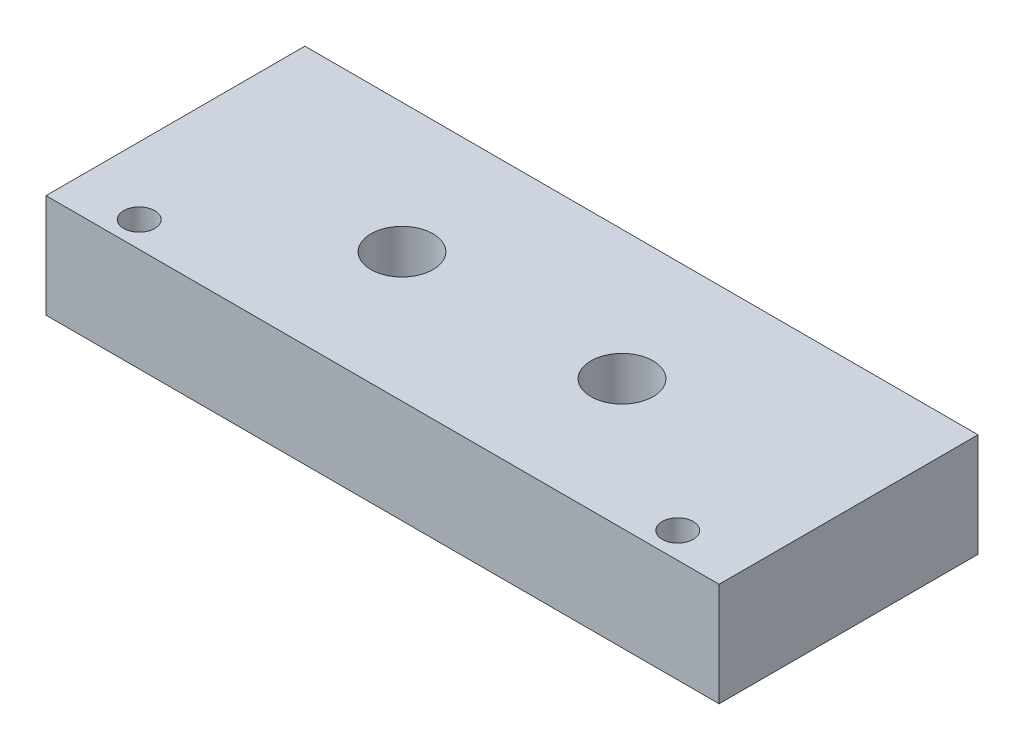
SolidWorks part; units mm, degrees
ref_plane "前视基准面" through (0, 0, 0) normal (0, 0, 1) x (1, 0, 0)
ref_plane "上视基准面" through (0, 0, 0) normal (0, 1, 0) x (1, 0, 0)
ref_plane "右视基准面" through (0, 0, 0) normal (1, 0, 0) x (0, 0, -1)
sketch "草图1" plane through (0, 0, 0) normal (0, 1, 0) x (1, 0, 0)
  line L0 (-10.625, 0) -> (10.625, 0) construction
  line L1 (-32.5, 12.5) -> (32.5, 12.5)
  line L2 (-32.5, 12.5) -> (-32.5, -12.5)
  line L3 (-32.5, -12.5) -> (32.5, -12.5)
  line L4 (32.5, 12.5) -> (32.5, -12.5)
  line L5 (-32.5, 12.5) -> (32.5, -12.5) construction
  line L6 (-32.5, -12.5) -> (32.5, 12.5) construction
  circle A0 centre (-10.625, 0) radius 3
  circle A1 centre (10.625, 0) radius 3
  point P0 (0, 0)
  point P9 (0, 0)
  dimension "D4" = 6
  dimension "D1" = 65
  dimension "D2" = 25
  dimension "D3" = 21.25
extrude "凸台-拉伸1" add sketch "草图1" along normal blind 10
sketch "草图2" plane through (0, 0, 0) normal (0, -1, 0) x (1, 0, 0)
  line L0 (0, 0) -> (0, 10) construction
  line L1 (-26, 10) -> (26, 10) construction
  line L3 (-32.5, -12.5) -> (-32.5, 12.5) construction
  line L4 (-32.5, 12.5) -> (32.5, 12.5) construction
  circle A0 centre (-26, 10) radius 1.5
  circle A1 centre (26, 10) radius 1.5
  point P5 (0, 10)
  dimension "D3" = 3
  dimension "D1" = 2.5
  dimension "D2" = 6.5
extrude "切除-拉伸1" cut sketch "草图2" against normal blind 10
